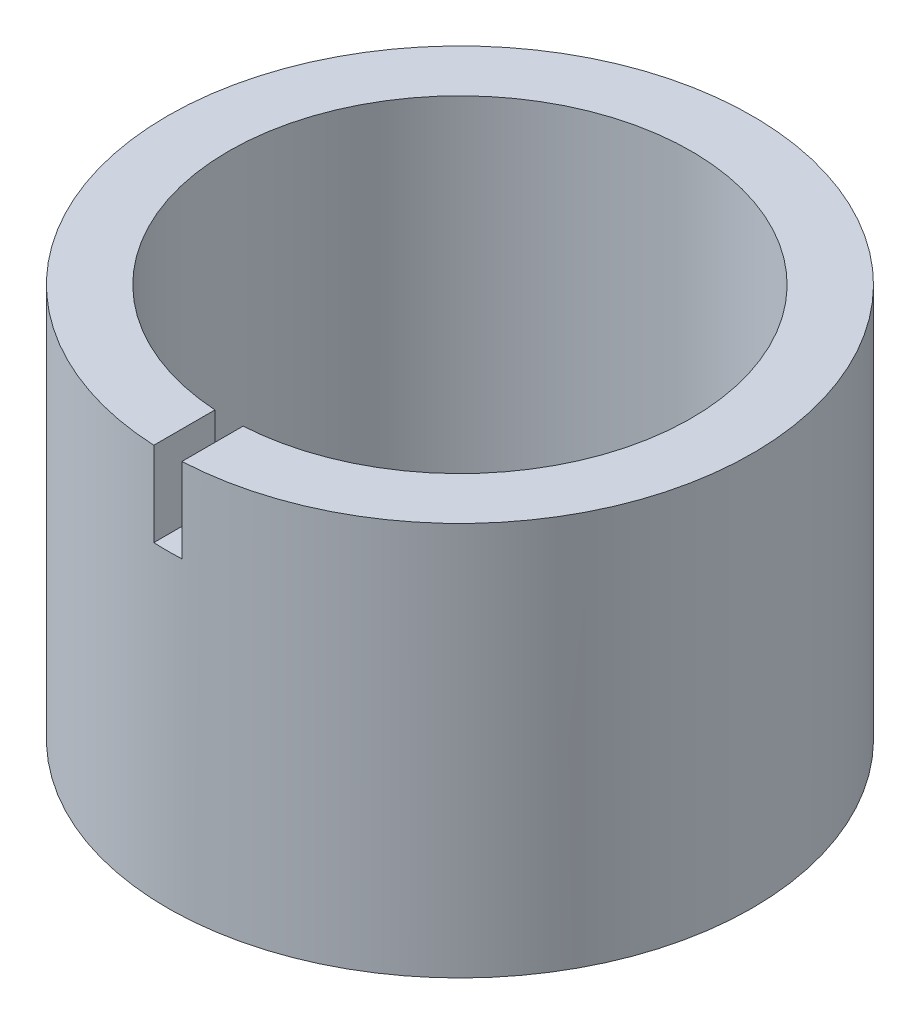
SolidWorks part; units mm, degrees
ref_plane "Front Plane" through (0, 0, 0) normal (0, 0, 1) x (1, 0, 0)
ref_plane "Top Plane" through (0, 0, 0) normal (0, 1, 0) x (1, 0, 0)
ref_plane "Right Plane" through (0, 0, 0) normal (1, 0, 0) x (0, 0, -1)
sketch "Sketch1" plane through (0, 0, 0) normal (0, 1, 0) x (1, 0, 0)
  circle A0 centre (0, 0) radius 10.45
  circle A1 centre (0, 0) radius 13.208
extrude "Boss-Extrude1" add sketch "Sketch1" along normal blind 17.78
sketch "Sketch2" plane through (0, 17.78, 0) normal (0, 1, 0) x (1, 0, 0)
  line L3 (-0.635, -13.6448) -> (0.635, -13.6448)
  line L4 (-0.635, -13.6448) -> (-0.635, -10.0577)
  line L5 (-0.635, -10.0577) -> (0.635, -10.0577)
  line L6 (0.635, -13.6448) -> (0.635, -10.0577)
  line L7 (-0.635, -13.6448) -> (0.635, -10.0577) construction
  line L8 (-0.635, -10.0577) -> (0.635, -13.6448) construction
  point P2 (0, -11.8513)
extrude "Cut-Extrude1" cut sketch "Sketch2" against normal blind 3.81
sketch "Sketch3" plane through (0, 0, 0) normal (0, -1, 0) x (1, 0, 0)
  line L2 (-0.635, -14.4981) -> (1.1714, -14.4981)
  line L3 (-0.635, -14.4981) -> (-0.635, -10.1988)
  line L4 (-0.635, -10.1988) -> (1.1714, -10.1988)
  line L5 (1.1714, -14.4981) -> (1.1714, -10.1988)
  line L6 (-0.635, -14.4981) -> (1.1714, -10.1988) construction
  line L7 (-0.635, -10.1988) -> (1.1714, -14.4981) construction
  point P3 (0.2682, -12.3484)
extrude "Cut-Extrude2" cut sketch "Sketch3" against normal blind 3.81
